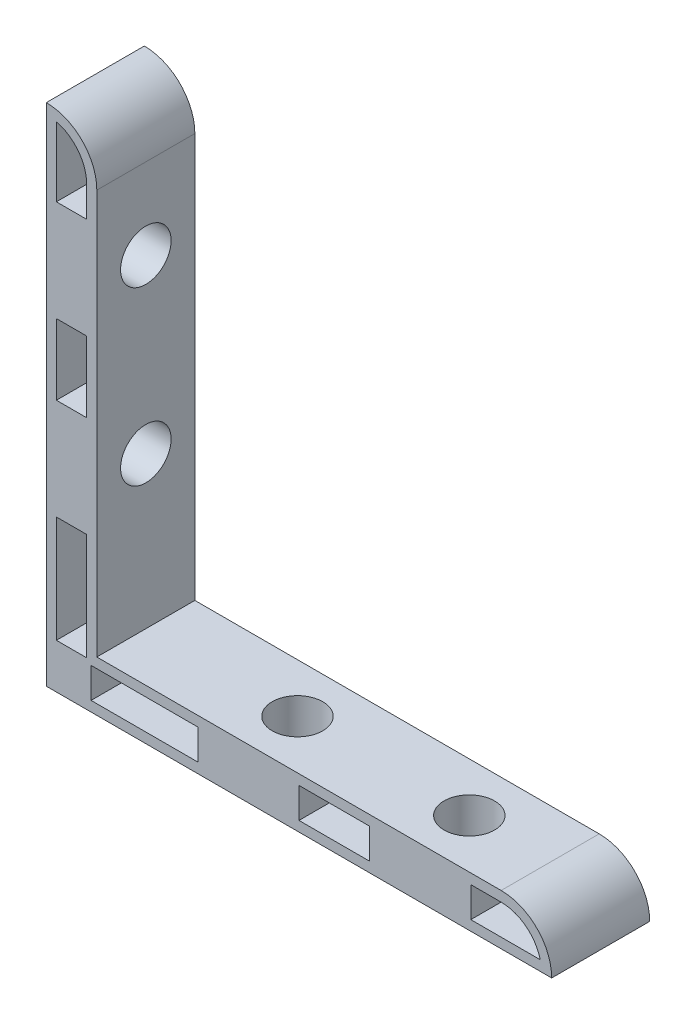
SolidWorks part; units mm, degrees
ref_plane "前视基准面" through (0, 0, 0) normal (0, 0, 1) x (1, 0, 0)
ref_plane "上视基准面" through (0, 0, 0) normal (0, 1, 0) x (1, 0, 0)
ref_plane "右视基准面" through (0, 0, 0) normal (1, 0, 0) x (0, 0, -1)
sketch "草图1" plane through (0, 0, 0) normal (0, 0, 1) x (1, 0, 0)
  line B0 (0, 50) -> (0, 0)
  line B1 (0, 0) -> (50, 0)
  line B2 (5, 45) -> (5, 5)
  line B3 (5, 5) -> (45, 5)
  arc B4 (5, 45) -> (0, 50) centre (0, 45) ccw
  arc B5 (50, 0) -> (45, 5) centre (45, 0) ccw
sketch_block_instance "A$C37CE760C-1"
sketch_block "A$C37CE760C"
extrude "凸台-拉伸1" add sketch "草图1" along normal mid plane 9.7
sketch "草图3" plane through (5, 0, 0) normal (1, 0, 0) x (0, 0, -1)
  line L0 (-4.85, 0) -> (4.85, 0) construction
  point P0 (0, 20)
  point P4 (0, 37)
  dimension "D1" = 20
  dimension "D2" = 2
hole_wizard "M6 螺纹孔1" positions "3D草图1" profile "草图4" tap size "M6" standard "Iso"
sketch3d "3D草图1"
  point P0 (5, 37, 0)
  point P3 (5, 20, 0)
sketch "草图4" plane through (5, 37, 0) normal (0, 1, 0) x (0, 0, -1)
  line L0 (0, 0) -> (0, 24.5022)
  line L1 (0, 24.5022) -> (2.5, 23)
  line L2 (2.5, 23) -> (2.5, 0)
  line L5 (2.5, 0) -> (0, 0)
  line L10 (0, 24.5022) -> (-2.5, 23) construction
  line L11 (0, -6.35) -> (0, 107.95) construction
  dimension "螺纹孔钻头直径" = 5
  dimension "螺纹孔钻头深度" = 23
  dimension "导头角度" = 118
cosmetic thread "孔螺蚊线1" parameters "D1"=5, "D2"=6
cosmetic thread "孔螺蚊线2" parameters "D1"=5, "D2"=6
sketch "草图5" plane through (0, 5, 0) normal (0, 1, 0) x (1, 0, 0)
  line L0 (0, -4.85) -> (0, 4.85) construction
  point P0 (20, 0)
  point P4 (37, 0)
  dimension "D1" = 20
  dimension "D2" = 2
hole_wizard "M6 螺纹孔2" positions "3D草图2" profile "草图6" tap size "M6" standard "Iso"
sketch3d "3D草图2"
  point P0 (20, 5, 0)
  point P3 (37, 5, 0)
sketch "草图6" plane through (20, 5, 0) normal (1, 0, 0) x (0, 0, 1)
  line L0 (0, 0) -> (0, 24.5022)
  line L1 (0, 24.5022) -> (2.5, 23)
  line L2 (2.5, 23) -> (2.5, 0)
  line L5 (2.5, 0) -> (0, 0)
  line L10 (0, 24.5022) -> (-2.5, 23) construction
  line L11 (0, -6.35) -> (0, 107.95) construction
  dimension "螺纹孔钻头直径" = 5
  dimension "螺纹孔钻头深度" = 23
  dimension "导头角度" = 118
cosmetic thread "孔螺蚊线3" parameters "D1"=5, "D2"=6
cosmetic thread "孔螺蚊线4" parameters "D1"=5, "D2"=6
sketch "草图7" plane through (0, 0, -4.85) normal (0, 0, -1) x (-1, 0, 0)
  line L2 (-4, 4.4325) -> (-4, 15)
  line L27 (-1, 15) -> (-4, 15)
  line L28 (-4.4325, 4) -> (-4.4325, 1)
  line L29 (-4, 42) -> (-1, 42)
  line L30 (-15, 1) -> (-15, 4)
  line L31 (-1, 42) -> (-1, 48.873)
  line L32 (-42, 4) -> (-42, 1)
  line L33 (-4.4325, 1) -> (-15, 1)
  line L34 (-42, 1) -> (-48.873, 1)
  line L36 (-25, 4) -> (-32, 4)
  line L37 (-1, 25) -> (-1, 32)
  line L38 (-4, 25) -> (-1, 25)
  line L39 (-1, 4.4325) -> (-1, 15)
  line L40 (-4, 4.4325) -> (-1, 4.4325)
  line L41 (-4.4325, 4) -> (-15, 4)
  line L42 (-4, 42) -> (-4, 45)
  line L43 (-42, 4) -> (-45, 4)
  line L44 (-25, 1) -> (-32, 1)
  line L45 (-25, 4) -> (-25, 1)
  line L46 (-4, 25) -> (-4, 32)
  line L47 (-32, 1) -> (-32, 4)
  line L48 (-1, 32) -> (-4, 32)
  arc A2 (-48.873, 1) -> (-45, 4) centre (-45, 0) cw
  arc A3 (-4, 45) -> (-1, 48.873) centre (0, 45) cw
extrude "切除-拉伸1" cut sketch "草图7" against normal blind 3
sketch "草图8" plane through (0, 0, 4.85) normal (0, 0, 1) x (1, 0, 0)
  line L1 (1, 42) -> (1, 48.873)
  line L25 (4, 42) -> (1, 42)
  line L26 (42, 4) -> (45, 4)
  line L27 (1, 15) -> (4, 15)
  line L28 (4, 4.4325) -> (4, 15)
  line L29 (42, 4) -> (42, 1)
  line L30 (1, 32) -> (4, 32)
  line L31 (15, 1) -> (15, 4)
  line L32 (4.4325, 4) -> (15, 4)
  line L33 (32, 1) -> (32, 4)
  line L34 (25, 4) -> (32, 4)
  line L36 (4, 42) -> (4, 45)
  line L37 (4, 4.4325) -> (1, 4.4325)
  line L38 (42, 1) -> (48.873, 1)
  line L39 (1, 4.4325) -> (1, 15)
  line L40 (4, 25) -> (1, 25)
  line L41 (4.4325, 4) -> (4.4325, 1)
  line L42 (1, 25) -> (1, 32)
  line L43 (4.4325, 1) -> (15, 1)
  line L44 (25, 4) -> (25, 1)
  line L45 (25, 1) -> (32, 1)
  line L46 (4, 25) -> (4, 32)
  arc A2 (48.873, 1) -> (45, 4) centre (45, 0) ccw
  arc A3 (4, 45) -> (1, 48.873) centre (0, 45) ccw
extrude "切除-拉伸2" cut sketch "草图8" against normal blind 3
